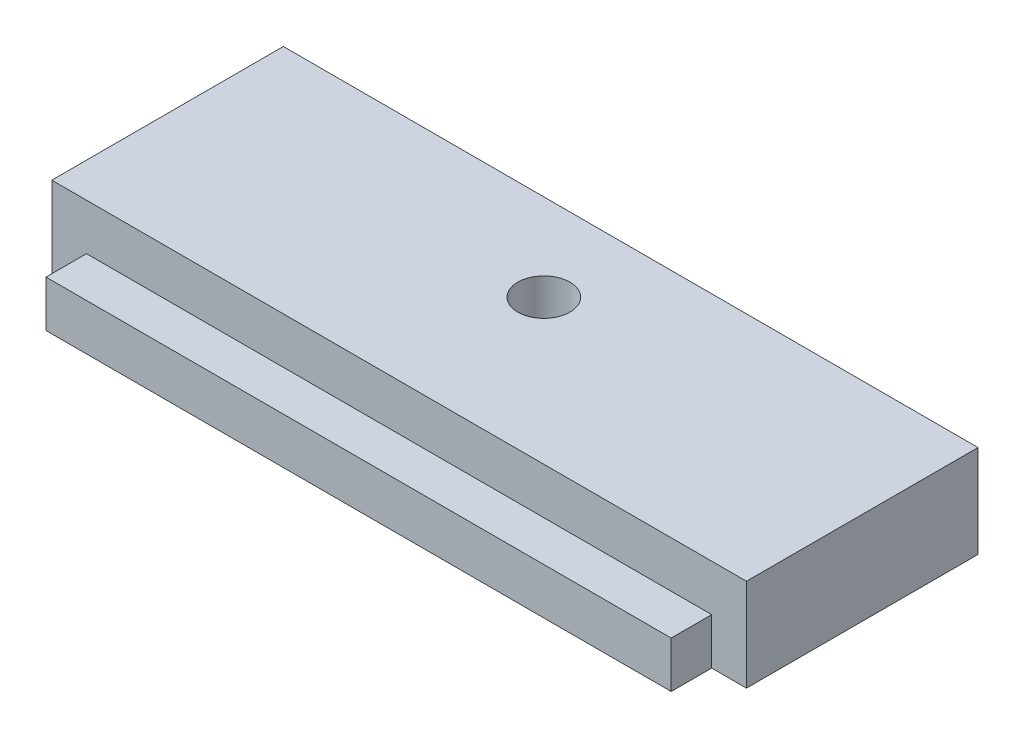
SolidWorks part; units mm, degrees
ref_plane "정면" through (0, 0, 0) normal (0, 0, 1) x (1, 0, 0)
ref_plane "윗면" through (0, 0, 0) normal (0, 1, 0) x (1, 0, 0)
ref_plane "우측면" through (0, 0, 0) normal (1, 0, 0) x (0, 0, -1)
sketch "스케치1" plane through (0, 0, 0) normal (0, 0, 1) x (1, 0, 0)
  line L0 (3, 0) -> (57, 0)
  line L1 (3, 0) -> (3, 4)
  line L2 (3, 4) -> (57, 4)
  line L3 (57, 0) -> (57, 4)
  line L4 (0, 0) -> (60, 0)
  line L5 (0, 0) -> (0, 8)
  line L6 (0, 8) -> (60, 8)
  line L7 (60, 0) -> (60, 8)
  dimension "D1" = 4
  dimension "D2" = 8
  dimension "D3" = 3
  dimension "D4" = 3
  dimension "D5" = 54
extrude "보스-돌출2" add sketch "스케치1" along normal blind 3.5 contours L0 L3 L2 L1
sketch "스케치2" plane through (0, 0, 0) normal (0, 0, -1) x (-1, 0, 0)
  line L0 (-60, 8) -> (0, 8)
  line L1 (-60, 8) -> (-60, -3)
  line L2 (-60, -3) -> (0, -3)
  line L3 (0, 8) -> (0, -3)
  line L4 (-3, 4) -> (-57, 4) construction
  line L5 (-3, 0) -> (-3, 4) construction
  dimension "D1" = 60
  dimension "D2" = 11
  dimension "D3" = 4
  dimension "D4" = 3
extrude "보스-돌출3" add sketch "스케치2" along normal blind 5
sketch "스케치3" plane through (0, 0, 0) normal (0, 0, 1) x (1, 0, 0)
  line L0 (60, 8) -> (60, -3) construction
  line L1 (0, -3) -> (60, -3)
  line L2 (0, -3) -> (0, 0)
  line L3 (0, 0) -> (60, 0)
  line L4 (60, -3) -> (60, 0)
  dimension "D1" = 3
extrude "컷-돌출1" cut sketch "스케치3" against normal blind 10
sketch "스케치4" plane through (0, 0, -5) normal (0, 0, -1) x (-1, 0, 0)
  line L4 (-60, 0) -> (0, 0)
  line L5 (0, 0) -> (0, 8)
  line L6 (0, 8) -> (-60, 8)
  line L7 (-60, 8) -> (-60, 0)
  line L8 (-60, 0) -> (0, 0)
  line L9 (0, 0) -> (0, 8)
  line L10 (0, 8) -> (-60, 8)
  line L11 (-60, 8) -> (-60, 0)
  dimension "D1" = 0
extrude "보스-돌출4" add sketch "스케치4" along normal blind 15
sketch "스케치5" plane through (0, 8, 0) normal (0, 1, 0) x (1, 0, 0)
  line L0 (0, 20) -> (60, 20) construction
  line L1 (60, 20) -> (60, 0) construction
  circle A0 centre (30, 12.5) radius 2.25
  dimension "D3" = 4.5
  dimension "D1" = 7.5
  dimension "D2" = 30
extrude "컷-돌출2" cut sketch "스케치5" against normal through all
